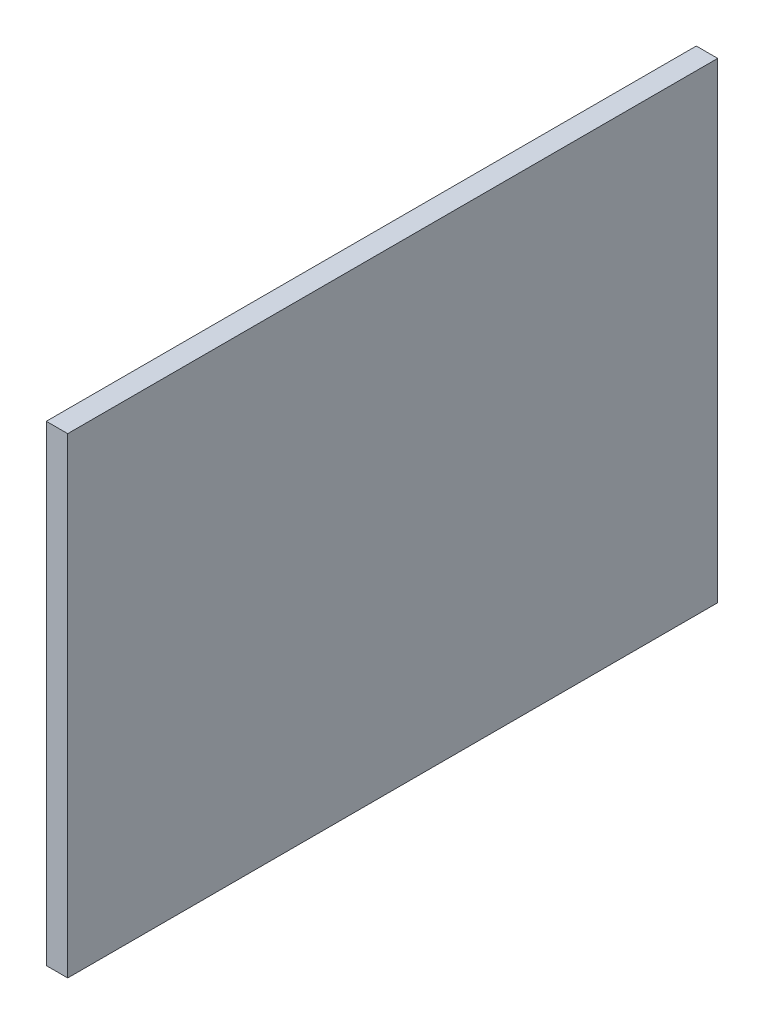
SolidWorks part; units mm, degrees
ref_plane "Front Plane" through (0, 0, 0) normal (0, 0, 1) x (1, 0, 0)
ref_plane "Top Plane" through (0, 0, 0) normal (0, 1, 0) x (1, 0, 0)
ref_plane "Right Plane" through (0, 0, 0) normal (1, 0, 0) x (0, 0, -1)
sketch "Sketch1" plane through (0, 0, 0) normal (1, 0, 0) x (0, 0, -1)
  line L1 (0, 0) -> (577.85, 0)
  line L2 (0, 0) -> (0, 419.1)
  line L3 (0, 419.1) -> (577.85, 419.1)
  line L4 (577.85, 0) -> (577.85, 419.1)
  dimension "D1" = 419.1
  dimension "D2" = 577.85
extrude "Boss-Extrude1" add sketch "Sketch1" along normal blind 19.05
